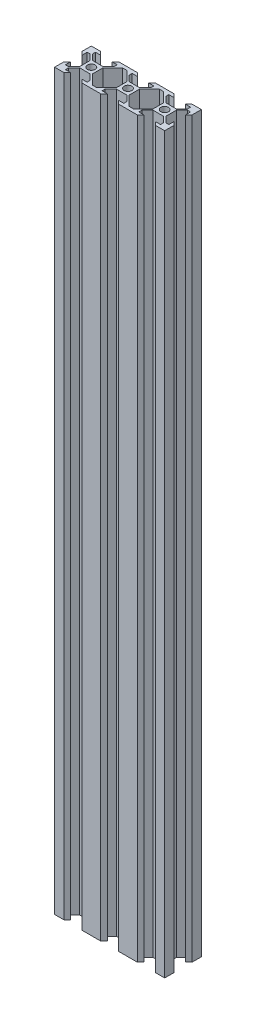
SolidWorks part; units mm, degrees
ref_plane "前视基准面" through (0, 0, 0) normal (0, 0, 1) x (1, 0, 0)
ref_plane "上视基准面" through (0, 0, 0) normal (0, 1, 0) x (1, 0, 0)
ref_plane "右视基准面" through (0, 0, 0) normal (1, 0, 0) x (0, 0, -1)
sketch "草图1" plane through (0, 0, 0) normal (0, 1, 0) x (1, 0, 0)
  line L0 (-25.721, 0) -> (73.7722, 0)
  line L1 (0, 21.255) -> (0, -16.6235)
  line L2 (-10, 21.255) -> (-10, -16.6235)
  line L3 (-25.721, 10) -> (73.7722, 10)
  line L4 (-4.9, 10) -> (-3.1, 8.2)
  line L5 (-3.1, 8.2) -> (-5.9236, 8.2)
  line L6 (-5.9236, 8.2) -> (-5.9236, 6.56)
  line L7 (-5.9236, 6.56) -> (-2.84, 3.4764)
  line L8 (-2.84, 3.4764) -> (2.84, 3.4764)
  line L9 (-10, 10) -> (0, 0) construction
  line L10 (5.9236, 6.56) -> (2.84, 3.4764)
  line L11 (5.9236, 8.2) -> (5.9236, 6.56)
  line L12 (3.1, 8.2) -> (5.9236, 8.2)
  line L13 (4.9, 10) -> (3.1, 8.2)
  line L14 (-10, -4.9) -> (-8.2, -3.1)
  line L15 (-8.2, -3.1) -> (-8.2, -5.9236)
  line L16 (-8.2, -5.9236) -> (-6.56, -5.9236)
  line L17 (-6.56, -5.9236) -> (-3.4764, -2.84)
  line L18 (-3.4764, 2.84) -> (-3.4764, -2.84)
  line L19 (-6.56, 5.9236) -> (-3.4764, 2.84)
  line L20 (-8.2, 5.9236) -> (-6.56, 5.9236)
  line L21 (-8.2, 3.1) -> (-8.2, 5.9236)
  line L22 (-10, 4.9) -> (-8.2, 3.1)
  line L23 (-25.721, -10) -> (73.7722, -10)
  line L24 (4.9, -10) -> (3.1, -8.2)
  line L25 (3.1, -8.2) -> (5.9236, -8.2)
  line L26 (5.9236, -8.2) -> (5.9236, -6.56)
  line L27 (5.9236, -6.56) -> (2.84, -3.4764)
  line L28 (-2.84, -3.4764) -> (2.84, -3.4764)
  line L29 (-5.9236, -6.56) -> (-2.84, -3.4764)
  line L30 (-5.9236, -8.2) -> (-5.9236, -6.56)
  line L31 (-3.1, -8.2) -> (-5.9236, -8.2)
  line L32 (-4.9, -10) -> (-3.1, -8.2)
  line L33 (50, 21.255) -> (50, -16.6235)
  line L34 (20, 21.255) -> (20, -16.6235)
  line L35 (10, 4.9) -> (8.2, 3.1)
  line L36 (8.2, 3.1) -> (8.2, 5.9236)
  line L37 (8.2, 5.9236) -> (6.56, 5.9236)
  line L38 (6.56, 5.9236) -> (3.4764, 2.84)
  line L39 (3.4764, 2.84) -> (3.4764, -2.84)
  line L40 (6.56, -5.9236) -> (3.4764, -2.84)
  line L41 (8.2, -5.9236) -> (6.56, -5.9236)
  line L42 (8.2, -3.1) -> (8.2, -5.9236)
  line L43 (10, -4.9) -> (8.2, -3.1)
  line L44 (15.1, 10) -> (16.9, 8.2)
  line L45 (16.9, 8.2) -> (14.0764, 8.2)
  line L46 (14.0764, 8.2) -> (14.0764, 6.56)
  line L47 (14.0764, 6.56) -> (17.16, 3.4764)
  line L48 (17.16, 3.4764) -> (22.84, 3.4764)
  line L49 (25.9236, 6.56) -> (22.84, 3.4764)
  line L50 (25.9236, 8.2) -> (25.9236, 6.56)
  line L51 (23.1, 8.2) -> (25.9236, 8.2)
  line L52 (24.9, 10) -> (23.1, 8.2)
  line L53 (10, -4.9) -> (11.8, -3.1)
  line L54 (11.8, -3.1) -> (11.8, -5.9236)
  line L55 (11.8, -5.9236) -> (13.44, -5.9236)
  line L56 (13.44, -5.9236) -> (16.5236, -2.84)
  line L57 (16.5236, 2.84) -> (16.5236, -2.84)
  line L58 (13.44, 5.9236) -> (16.5236, 2.84)
  line L59 (11.8, 5.9236) -> (13.44, 5.9236)
  line L60 (11.8, 3.1) -> (11.8, 5.9236)
  line L61 (10, 4.9) -> (11.8, 3.1)
  line L62 (24.9, -10) -> (23.1, -8.2)
  line L63 (23.1, -8.2) -> (25.9236, -8.2)
  line L64 (25.9236, -8.2) -> (25.9236, -6.56)
  line L65 (25.9236, -6.56) -> (22.84, -3.4764)
  line L66 (17.16, -3.4764) -> (22.84, -3.4764)
  line L67 (14.0764, -6.56) -> (17.16, -3.4764)
  line L68 (14.0764, -8.2) -> (14.0764, -6.56)
  line L69 (16.9, -8.2) -> (14.0764, -8.2)
  line L70 (15.1, -10) -> (16.9, -8.2)
  line L71 (30, 4.9) -> (28.2, 3.1)
  line L72 (28.2, 3.1) -> (28.2, 5.9236)
  line L73 (28.2, 5.9236) -> (26.56, 5.9236)
  line L74 (26.56, 5.9236) -> (23.4764, 2.84)
  line L75 (23.4764, 2.84) -> (23.4764, -2.84)
  line L76 (26.56, -5.9236) -> (23.4764, -2.84)
  line L77 (28.2, -5.9236) -> (26.56, -5.9236)
  line L78 (28.2, -3.1) -> (28.2, -5.9236)
  line L79 (30, -4.9) -> (28.2, -3.1)
  line L80 (6.56, 5.9236) -> (8.8364, 8.2)
  line L81 (35.1, 10) -> (36.9, 8.2)
  line L82 (36.9, 8.2) -> (34.0764, 8.2)
  line L83 (34.0764, 8.2) -> (34.0764, 6.56)
  line L84 (34.0764, 6.56) -> (37.16, 3.4764)
  line L85 (37.16, 3.4764) -> (42.84, 3.4764)
  line L86 (45.9236, 6.56) -> (42.84, 3.4764)
  line L87 (45.9236, 8.2) -> (45.9236, 6.56)
  line L88 (43.1, 8.2) -> (45.9236, 8.2)
  line L89 (44.9, 10) -> (43.1, 8.2)
  line L90 (30, -4.9) -> (31.8, -3.1)
  line L91 (31.8, -3.1) -> (31.8, -5.9236)
  line L92 (31.8, -5.9236) -> (33.44, -5.9236)
  line L93 (33.44, -5.9236) -> (36.5236, -2.84)
  line L94 (36.5236, 2.84) -> (36.5236, -2.84)
  line L95 (33.44, 5.9236) -> (36.5236, 2.84)
  line L96 (31.8, 5.9236) -> (33.44, 5.9236)
  line L97 (31.8, 3.1) -> (31.8, 5.9236)
  line L98 (30, 4.9) -> (31.8, 3.1)
  line L99 (44.9, -10) -> (43.1, -8.2)
  line L100 (43.1, -8.2) -> (45.9236, -8.2)
  line L101 (45.9236, -8.2) -> (45.9236, -6.56)
  line L102 (45.9236, -6.56) -> (42.84, -3.4764)
  line L103 (37.16, -3.4764) -> (42.84, -3.4764)
  line L104 (34.0764, -6.56) -> (37.16, -3.4764)
  line L105 (34.0764, -8.2) -> (34.0764, -6.56)
  line L106 (36.9, -8.2) -> (34.0764, -8.2)
  line L107 (35.1, -10) -> (36.9, -8.2)
  line L108 (50, 4.9) -> (48.2, 3.1)
  line L109 (48.2, 3.1) -> (48.2, 5.9236)
  line L110 (48.2, 5.9236) -> (46.56, 5.9236)
  line L111 (46.56, 5.9236) -> (43.4764, 2.84)
  line L112 (43.4764, 2.84) -> (43.4764, -2.84)
  line L113 (46.56, -5.9236) -> (43.4764, -2.84)
  line L114 (48.2, -5.9236) -> (46.56, -5.9236)
  line L115 (48.2, -3.1) -> (48.2, -5.9236)
  line L116 (50, -4.9) -> (48.2, -3.1)
  line L117 (13.44, 5.9236) -> (11.1636, 8.2)
  line L118 (30, 10) -> (40, 0) construction
  line L119 (10, 10) -> (20, 0) construction
  line L120 (8.8364, 8.2) -> (11.1636, 8.2)
  line L121 (8.8364, -8.2) -> (11.1636, -8.2)
  line L122 (6.56, -5.9236) -> (8.8364, -8.2)
  line L123 (13.44, -5.9236) -> (11.1636, -8.2)
  line L124 (26.56, 5.9236) -> (28.8364, 8.2)
  line L125 (28.8364, 8.2) -> (31.1636, 8.2)
  line L126 (33.44, 5.9236) -> (31.1636, 8.2)
  line L127 (26.56, -5.9236) -> (28.8364, -8.2)
  line L128 (28.8364, -8.2) -> (31.1636, -8.2)
  line L129 (33.44, -5.9236) -> (31.1636, -8.2)
  circle A0 centre (0, 0) radius 2.1
  circle A1 centre (20, 0) radius 2.1
  circle A2 centre (40, 0) radius 2.1
  circle A3 centre (20, 0) radius 2.1
  circle A4 centre (40, 0) radius 2.1
  point P22 (0, 3.4764)
  point P37 (-3.4764, 0)
  point P50 (0, -3.4764)
  point P65 (3.4764, 0)
  point P77 (20, 3.4764)
  point P92 (16.5236, 0)
  point P103 (20, -3.4764)
  point P114 (23.4764, 0)
  point P124 (40, 3.4764)
  point P139 (36.5236, 0)
  point P150 (40, -3.4764)
  point P161 (43.4764, 0)
  dimension "D1" = 3
  dimension "D2" = 4.2
  dimension "D3" = 20
  dimension "D6" = 1.8
  dimension "D7" = 1.64
  dimension "D8" = 2.84
  dimension "D9" = 3.1
  dimension "D10" = 45
  dimension "D11" = 0.9
  dimension "D16" = 2
  dimension "D4" = 10
  dimension "D5" = 10
  dimension "D12" = 10
  dimension "D13" = 60
  dimension "D14" = 30
  dimension "D15" = 3
extrude "凸台-拉伸1" add sketch "草图1" along normal blind 400 contours A0 L1 L8 L7 L6 L5 L4 L3 L2 L22 L21 L20 L19 L18 L0 | A0 L0 L18 L17 L16 L15 L14 L2 L23 L32 L31 L30 L29 L28 L1 | A1 L0 L57 L56 L123 L121 L122 L40 L39 A0 L1 L28 L27 L26 L25 L24 L23 L70 L69 L68 L67 L66 L34 | A1 L34 L48 L47 L46 L45 L44 L3 L13 L12 L11 L10 L8 L1 A0 L0 L39 L38 L80 L120 L117 L58 L57 | A2 L0 L112 L111 L110 L109 L108 L33 L3 L89 L88 L87 L86 L85 L84 L83 L82 L81 L52 L51 L50 L49 L48 L34 A1 L75 L74 L124 L125 L126 L95 L94 | A2 L0 L94 L93 L129 L128 L127 L76 L75 A1 L34 L66 L65 L64 L63 L62 L23 L107 L106 L105 L104 L103 L102 L101 L100 L99 L33 L116 L115 L114 L113 L112
